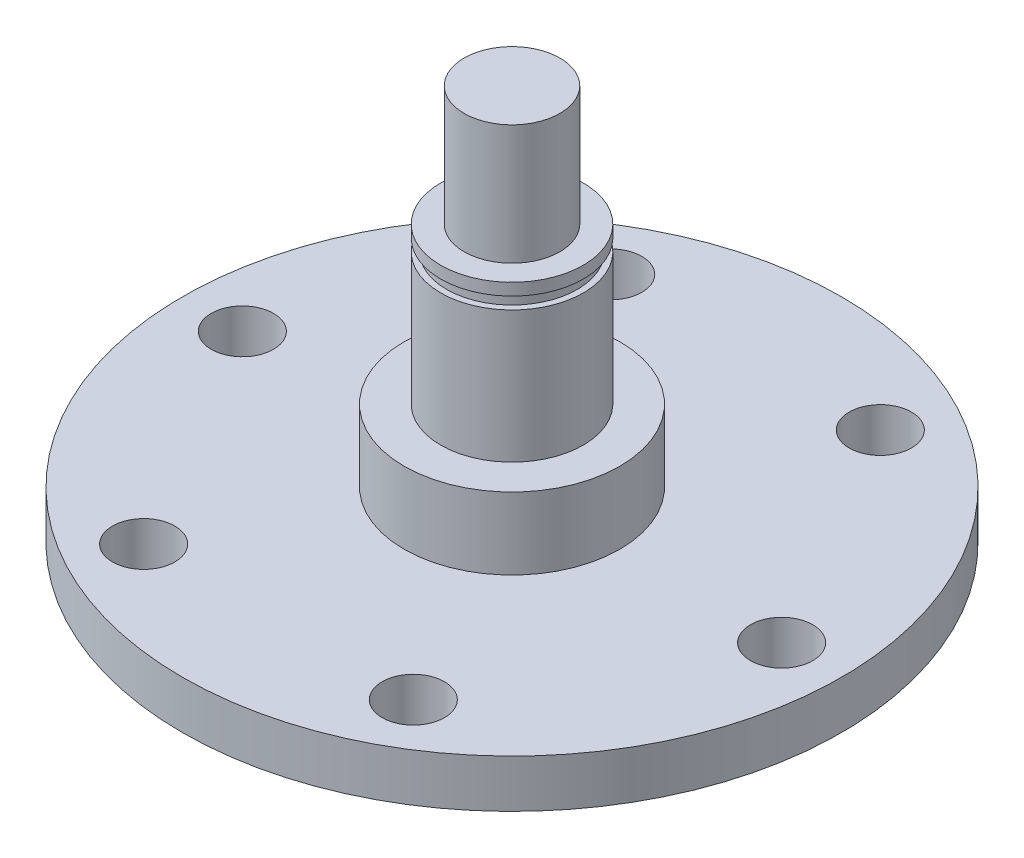
SolidWorks part; units mm, degrees
material "延性铁"
ref_plane "前视基准面" through (0, 0, 0) normal (0, 0, 1) x (1, 0, 0)
ref_plane "上视基准面" through (0, 0, 0) normal (0, 1, 0) x (1, 0, 0)
ref_plane "右视基准面" through (0, 0, 0) normal (1, 0, 0) x (0, 0, -1)
sketch "草图1" plane through (0, 0, 0) normal (0, 0, 1) x (1, 0, 0)
  line L0 (0, 0) -> (27.5, 0)
  line L1 (27.5, 0) -> (27.5, 4)
  line L2 (27.5, 4) -> (9, 4)
  line L3 (9, 4) -> (9, 10)
  line L4 (9, 10) -> (5.95, 10)
  line L5 (5.95, 10) -> (5.95, 21)
  line L6 (5.95, 21) -> (5.45, 21)
  line L7 (5.45, 21) -> (5.45, 22)
  line L8 (5.45, 22) -> (5.95, 22)
  line L9 (5.95, 22) -> (5.95, 23)
  line L10 (5.95, 23) -> (4, 23)
  line L11 (0, 23.5) -> (0, 0)
  line L12 (4, 23) -> (4, 33)
  line L13 (4, 33) -> (0, 33)
  line L14 (0, 33) -> (0, 23.5)
  dimension "D1" = 11
  dimension "D2" = 4
  dimension "D3" = 6
  dimension "D4" = 27.5
  dimension "D5" = 1
  dimension "D6" = 1
  dimension "D7" = 0.5
  dimension "D8" = 10
  dimension "D9" = 9
  dimension "D11" = 5.95
  dimension "D12" = 4
revolve "旋转1" add sketch "草图1" angle 360 about L11
sketch "草图2" plane through (0, 4, 0) normal (0, 1, 0) x (1, 0, 0)
  circle A0 centre (22.5, 0) radius 2.6
  circle A1 centre (11.25, -19.4856) radius 2.6
  circle A2 centre (-11.25, -19.4856) radius 2.6
  circle A3 centre (-22.5, 0) radius 2.6
  circle A4 centre (-11.25, 19.4856) radius 2.6
  circle A5 centre (11.25, 19.4856) radius 2.6
  point P15 (0, 0)
  dimension "D1" = 6
extrude "切除-拉伸1" cut sketch "草图2" against normal through all
